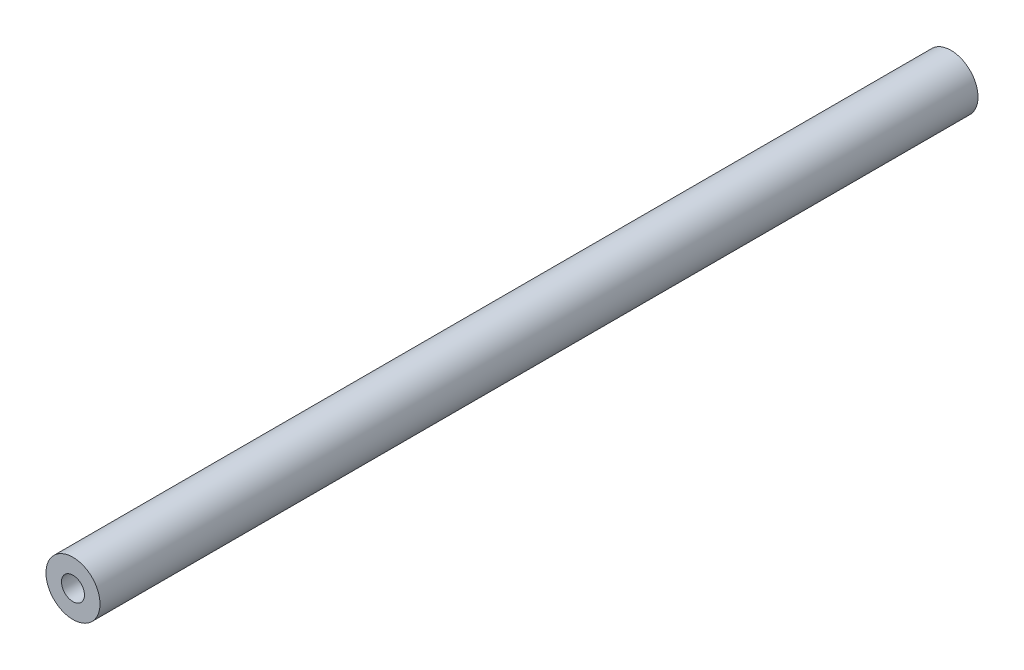
SolidWorks part; units mm, degrees
ref_plane "前视基准面" through (0, 0, 0) normal (0, 0, 1) x (1, 0, 0)
ref_plane "上视基准面" through (0, 0, 0) normal (0, 1, 0) x (1, 0, 0)
ref_plane "右视基准面" through (0, 0, 0) normal (1, 0, 0) x (0, 0, -1)
sketch "草图1" plane through (0, 0, 0) normal (0, 0, 1) x (1, 0, 0)
  circle A0 centre (0, 0) radius 8
  dimension "D1" = 16
extrude "凸台-拉伸1" add sketch "草图1" along normal blind 260
hole_wizard "M8 螺纹孔1" positions "3D草图2" profile "草图5" tap size "M8" standard "Gb"
sketch3d "3D草图2"
  line L0 (0, 0, 260) -> (0, 0, 0) construction
  point P0 (0, 0, 260)
  point P4 (0, 0, 0)
  point P8 (0, 0, 0)
  point P10 (0, 0, 0)
sketch "草图5" plane through (0, 0, 260) normal (1, 0, 0) x (0, -1, 0)
  line L0 (0, 0) -> (0, 28.2929)
  line L1 (0, 28.2929) -> (3.4, 26.25)
  line L2 (3.4, 26.25) -> (3.4, 0)
  line L5 (3.4, 0) -> (0, 0)
  line L10 (0, 28.2929) -> (-3.4, 26.25) construction
  line L11 (0, -6.35) -> (0, 107.95) construction
  dimension "螺纹孔钻头直径" = 6.8
  dimension "螺纹孔钻头深度" = 26.25
  dimension "导头角度" = 118
cosmetic thread "孔螺蚊线1"
cosmetic thread "孔螺蚊线2"
cosmetic thread "孔螺蚊线3"
cosmetic thread "孔螺蚊线4"
hole_wizard "M8 螺纹孔2" positions "草图7" profile "草图6" tap size "M8" standard "Gb"
sketch "草图7" plane through (0, 0, 0) normal (0, 0, -1) x (-1, 0, 0)
  point P0 (0, 0)
sketch "草图6" plane through (0, 0, 0) normal (1, 0, 0) x (0, 1, 0)
  line L0 (0, 0) -> (0, 28.2929)
  line L1 (0, 28.2929) -> (3.4, 26.25)
  line L2 (3.4, 26.25) -> (3.4, 0)
  line L5 (3.4, 0) -> (0, 0)
  line L10 (0, 28.2929) -> (-3.4, 26.25) construction
  line L11 (0, -6.35) -> (0, 107.95) construction
  dimension "螺纹孔钻头直径" = 6.8
  dimension "螺纹孔钻头深度" = 26.25
  dimension "导头角度" = 118
cosmetic thread "孔螺蚊线5"
